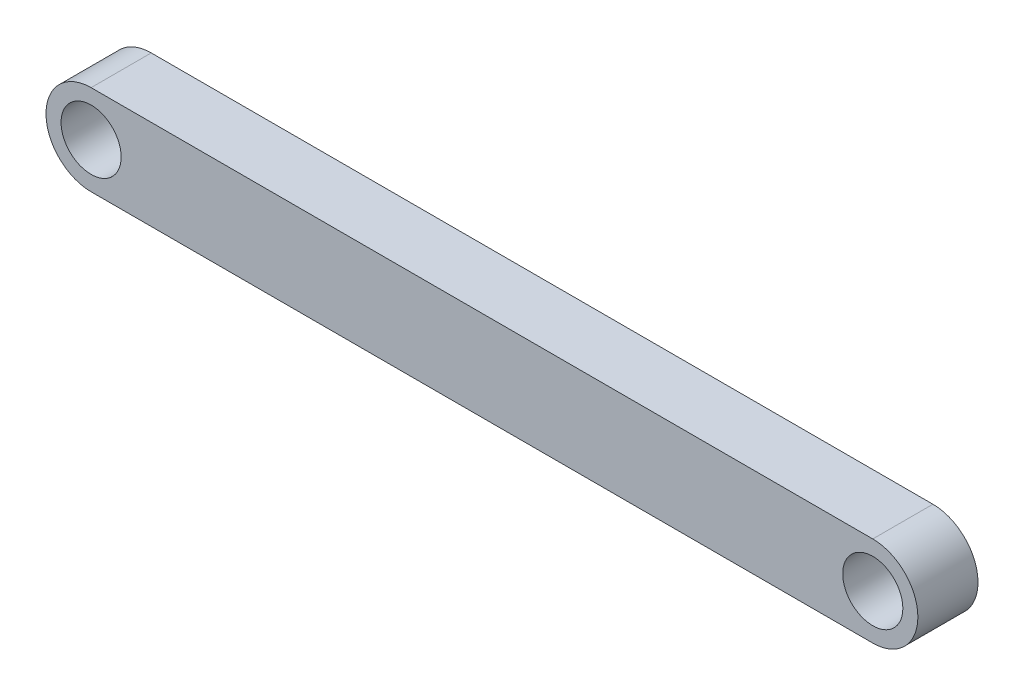
SolidWorks part; units mm, degrees
ref_plane "Front Plane" through (0, 0, 0) normal (0, 0, 1) x (1, 0, 0)
ref_plane "Top Plane" through (0, 0, 0) normal (0, 1, 0) x (1, 0, 0)
ref_plane "Right Plane" through (0, 0, 0) normal (1, 0, 0) x (0, 0, -1)
sketch "Sketch2" plane through (0, 0, 0) normal (0, 0, 1) x (1, 0, 0)
  line L0 (0, 0) -> (82.55, 0) construction
  line L1 (0, 4.7625) -> (82.55, 4.7625)
  line L2 (0, -4.7625) -> (82.55, -4.7625)
  arc A0 (0, 4.7625) -> (0, -4.7625) centre (0, 0) ccw
  arc A1 (82.55, -4.7625) -> (82.55, 4.7625) centre (82.55, 0) ccw
  circle A2 centre (82.55, 0) radius 3.175
  circle A3 centre (0, 0) radius 3.175
  point P3 (41.275, 0)
  dimension "D2" = 4.7625
  dimension "D3" = 6.35
  dimension "D4" = 6.35
  dimension "D1" = 82.55
extrude "Boss-Extrude1" add sketch "Sketch2" along normal blind 6.35
